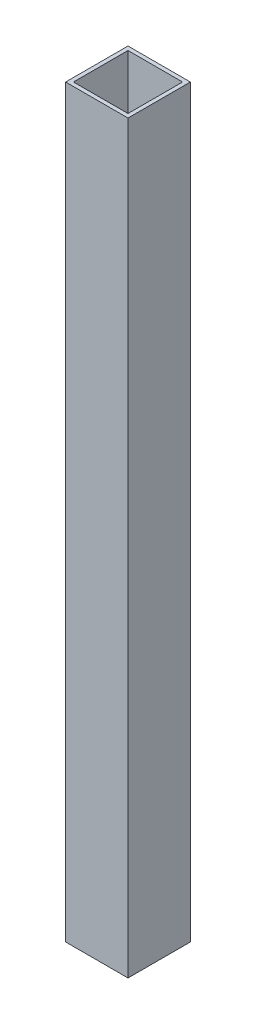
SolidWorks part; units mm, degrees
ref_plane "Alzado" through (0, 0, 0) normal (0, 0, 1) x (1, 0, 0)
ref_plane "Planta" through (0, 0, 0) normal (0, 1, 0) x (1, 0, 0)
ref_plane "Vista lateral" through (0, 0, 0) normal (1, 0, 0) x (0, 0, -1)
sketch "Croquis1" plane through (0, 0, 0) normal (0, 1, 0) x (1, 0, 0)
  line L0 (4.7625, -4.7625) -> (71.4375, -4.7625)
  line L1 (0, 0) -> (76.2, 0)
  line L2 (0, 0) -> (0, -76.2)
  line L3 (0, -76.2) -> (76.2, -76.2)
  line L4 (76.2, 0) -> (76.2, -76.2)
  line L5 (71.4375, -4.7625) -> (71.4375, -71.4375)
  line L6 (4.7625, -71.4375) -> (71.4375, -71.4375)
  line L7 (4.7625, -4.7625) -> (4.7625, -71.4375)
  dimension "D1" = 76.2
  dimension "D2" = 76.2
  dimension "D3" = 4.7625
extrude "Saliente-Extruir1" add sketch "Croquis1" along normal blind 910
